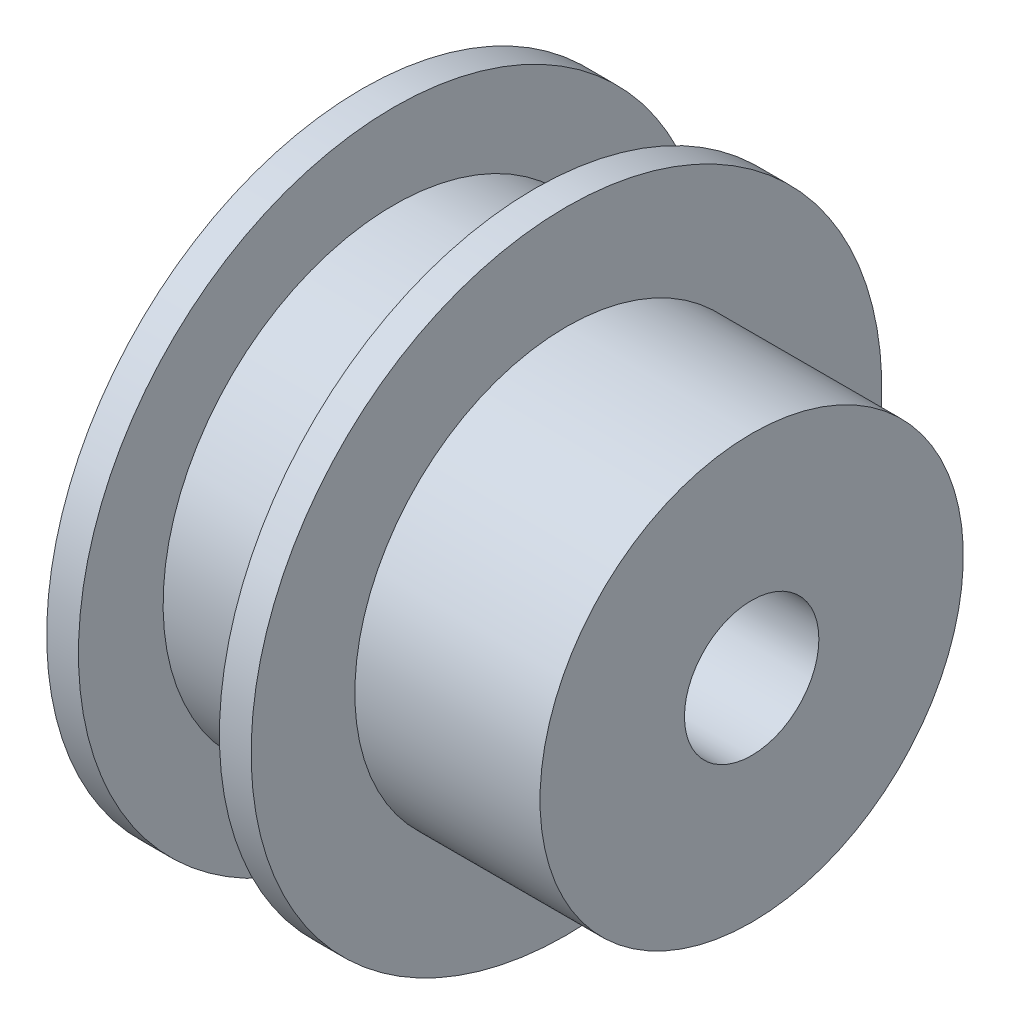
SolidWorks part; units mm, degrees
ref_plane "Front Plane" through (0, 0, 0) normal (0, 0, 1) x (1, 0, 0)
ref_plane "Top Plane" through (0, 0, 0) normal (0, 1, 0) x (1, 0, 0)
ref_plane "Right Plane" through (0, 0, 0) normal (1, 0, 0) x (0, 0, -1)
sketch "Sketch1" plane through (0, 0, 0) normal (0, 0, 1) x (1, 0, 0)
  line L0 (-3.33, 0) -> (3.33, 0)
  line L1 (-3.33, 0) -> (-3.33, 4)
  line L2 (-3.33, 4) -> (-4.83, 4)
  line L3 (-4.83, 4) -> (-4.83, -10.9)
  line L4 (-4.83, -10.9) -> (13.58, -10.9)
  line L5 (13.58, -10.9) -> (13.58, -0.9)
  line L6 (13.58, -0.9) -> (4.83, -0.9)
  line L7 (4.83, -0.9) -> (4.83, 4)
  line L8 (4.83, 4) -> (3.33, 4)
  line L9 (3.33, 4) -> (3.33, 0)
  point P3 (0, 0)
  point P4 (0, 0)
  dimension "D1" = 14.9
  dimension "D2" = 1.5
  dimension "D3" = 10
  dimension "D4" = 4
  dimension "D5" = 6.66
  dimension "D6" = 8.75
revolve "Revolve1" add sketch "Sketch1" angle 360 about L4
sketch "Sketch4" plane through (13.58, 0, 0) normal (1, 0, 0) x (0, 0, -1)
  line L0 (0, -0.9) -> (0, -10.9) construction
  circle A0 centre (0, -10.9) radius 10 construction
  circle A1 centre (0, -10.9) radius 3.175
  dimension "D1" = 6.35
extrude "Cut-Extrude1" cut sketch "Sketch4" against normal through all both and the other way through all
